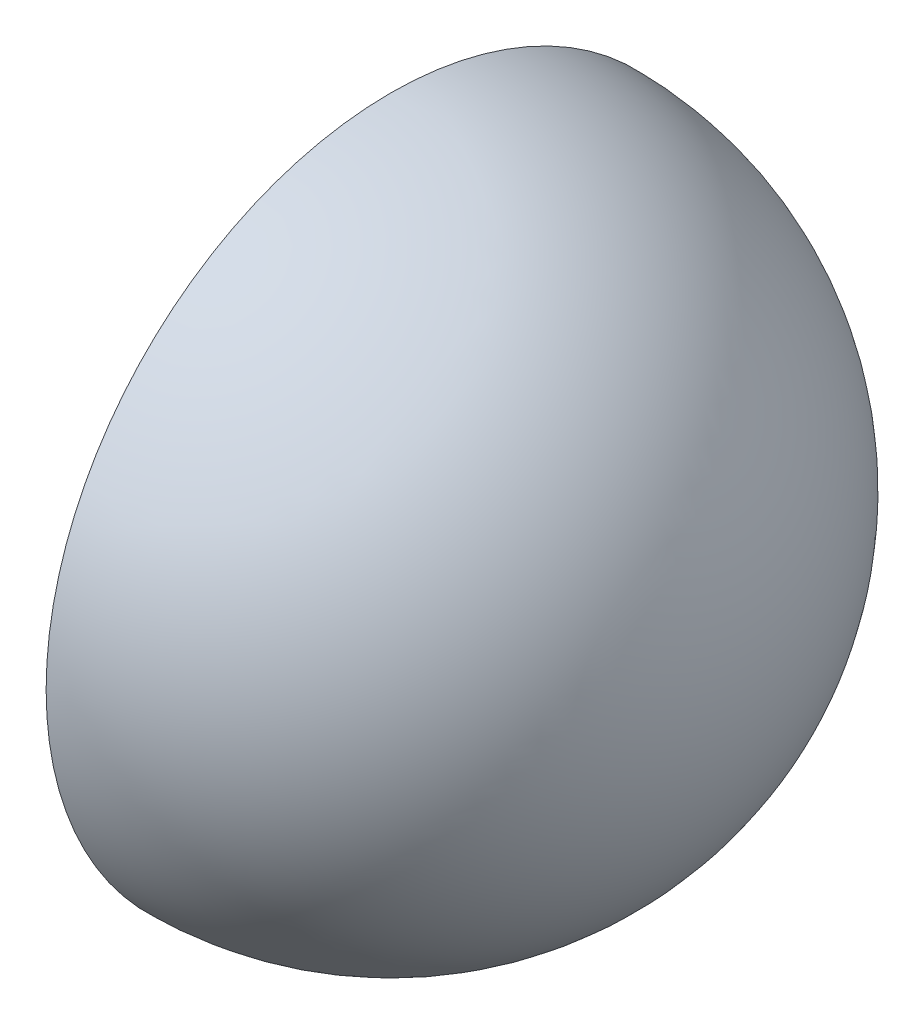
SolidWorks part; units mm, degrees
other "Camera1"
ref_plane "Front Plane" through (0, 0, 0) normal (0, 0, 1) x (1, 0, 0)
ref_plane "Top Plane" through (0, 0, 0) normal (0, 1, 0) x (1, 0, 0)
ref_plane "Right Plane" through (0, 0, 0) normal (1, 0, 0) x (0, 0, -1)
sketch "Sketch2" plane through (0, 0, 0) normal (0, 1, 0) x (1, 0, 0)
  line L0 (0, 0) -> (13, 0) construction
  line L1 (13, 0) -> (17, 0) construction
  line L2 (0, 0) -> (0, 19.0428) construction
  arc A1 (0, 17) -> (17, 0) centre (0, 0) cw
  dimension "D1" = 17
sketch "Sketch3" plane through (0, 0, 0) normal (0, 0, 1) x (1, 0, 0)
  line L0 (0, 0) -> (16, 0) construction
  line L1 (16, 0) -> (18, 0) construction
  line L2 (0, 0) -> (0, 19.0428) construction
  arc A0 (0, 16) -> (16, 0) centre (0, 0) cw
  arc A1 (0, 18) -> (18, 0) centre (0, 0) cw
  dimension "D2" = 2
  dimension "D1" = 16
revolve "Revolve-Thin4" add sketch "Sketch2" angle 360 about L1
